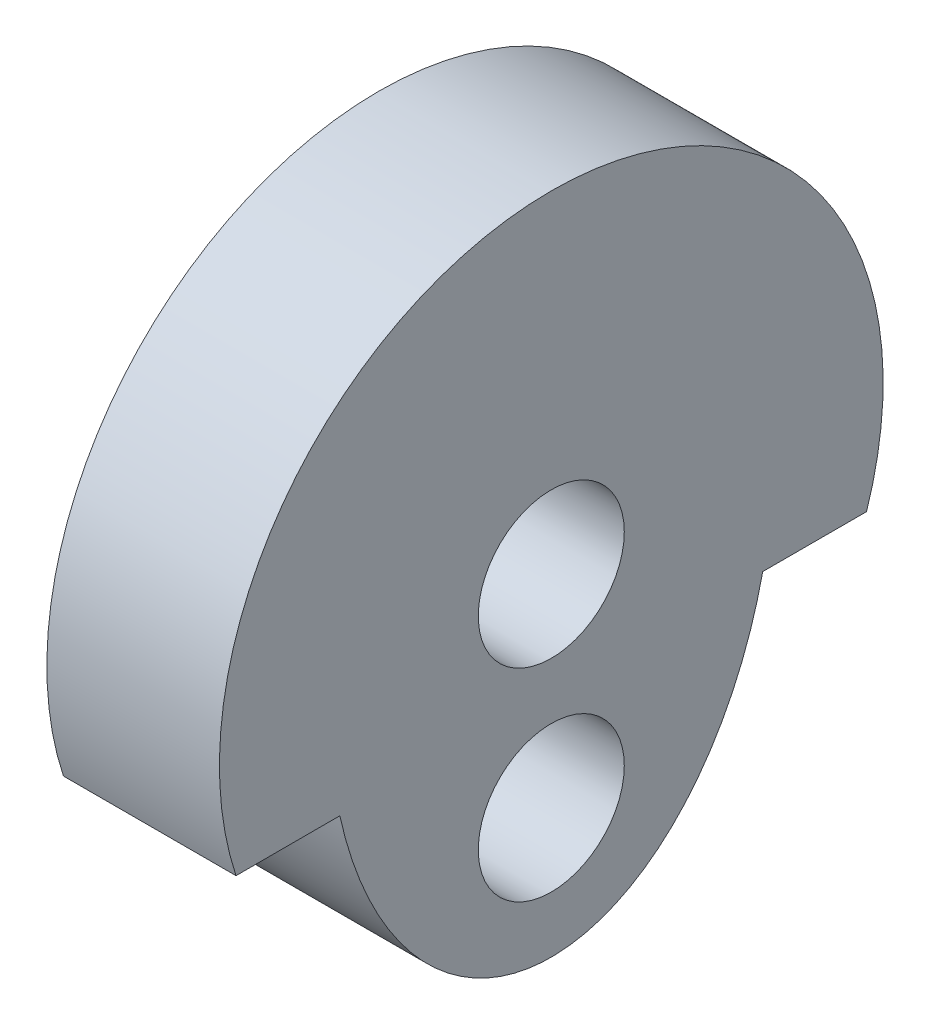
SolidWorks part; units mm, degrees
ref_plane "정면" through (0, 0, 0) normal (0, 0, 1) x (1, 0, 0)
ref_plane "윗면" through (0, 0, 0) normal (0, 1, 0) x (1, 0, 0)
ref_plane "우측면" through (0, 0, 0) normal (1, 0, 0) x (0, 0, -1)
sketch "Sketch1" plane through (0, 0, 0) normal (1, 0, 0) x (0, 0, -1)
  line L0 (-23.75, -7.8063) -> (-15.9298, -7.8063)
  line L1 (15.9298, -7.8063) -> (23.75, -7.8063)
  arc A0 (23.75, -7.8063) -> (-23.75, -7.8063) centre (0, 0) ccw
  ellipse E0 centre (0, 0) end of major axis (0, -25) minor radius 16.7682 (-15.9298, -7.8063) -> (15.9298, -7.8063) ccw
  dimension "D1" = 50
extrude "Boss-Extrude1" add sketch "Sketch1" along normal blind 13
hole_wizard "M10 Clearance Hole2" positions "3DSketch1" profile "Sketch2" hole size "M10" standard "Ansi Metric" end condition through all
sketch3d "3DSketch1"
  point P0 (0, 0, 0)
  point P3 (13, 0, 0)
sketch "Sketch2" plane through (13, 0, 0) normal (0, 1, 0) x (0, 0, -1)
  line L0 (0, 0) -> (0, 13)
  line L1 (0, 13) -> (5.5, 13)
  line L2 (5.5, 13) -> (5.5, 0)
  line L5 (5.5, 0) -> (0, 0)
  line L11 (0, -6.35) -> (0, 107.95) construction
  dimension "관통 구멍 지름" = 11
  dimension "관통 구멍 깊이" = 13
sketch "Sketch5" plane through (13, 0, 0) normal (1, 0, 0) x (0, 0, -1)
  line L0 (0, -5.5) -> (0, -25) construction
  circle A0 centre (0, 0) radius 5.5 construction
  ellipse E0 centre (0, 0) end of major axis (0, -25) minor radius 16.7682 (-15.9298, -7.8063) -> (15.9298, -7.8063) ccw construction
hole_wizard "M10 Clearance Hole1" positions "3DSketch6" profile "Sketch7" hole size "M10" standard "Ansi Metric" end condition through all
sketch3d "3DSketch6"
  line L0 (13, -5.5, 0) -> (13, -25, 0) construction
  point P0 (13, -15.25, 0)
  point P4 (13, -15.25, 0)
sketch "Sketch7" plane through (13, -15.25, 0) normal (0, 1, 0) x (0, 0, -1)
  line L0 (0, 0) -> (0, 13)
  line L1 (0, 13) -> (5.5, 13)
  line L2 (5.5, 13) -> (5.5, 0)
  line L5 (5.5, 0) -> (0, 0)
  line L11 (0, -6.35) -> (0, 107.95) construction
  dimension "관통 구멍 지름" = 11
  dimension "관통 구멍 깊이" = 13
